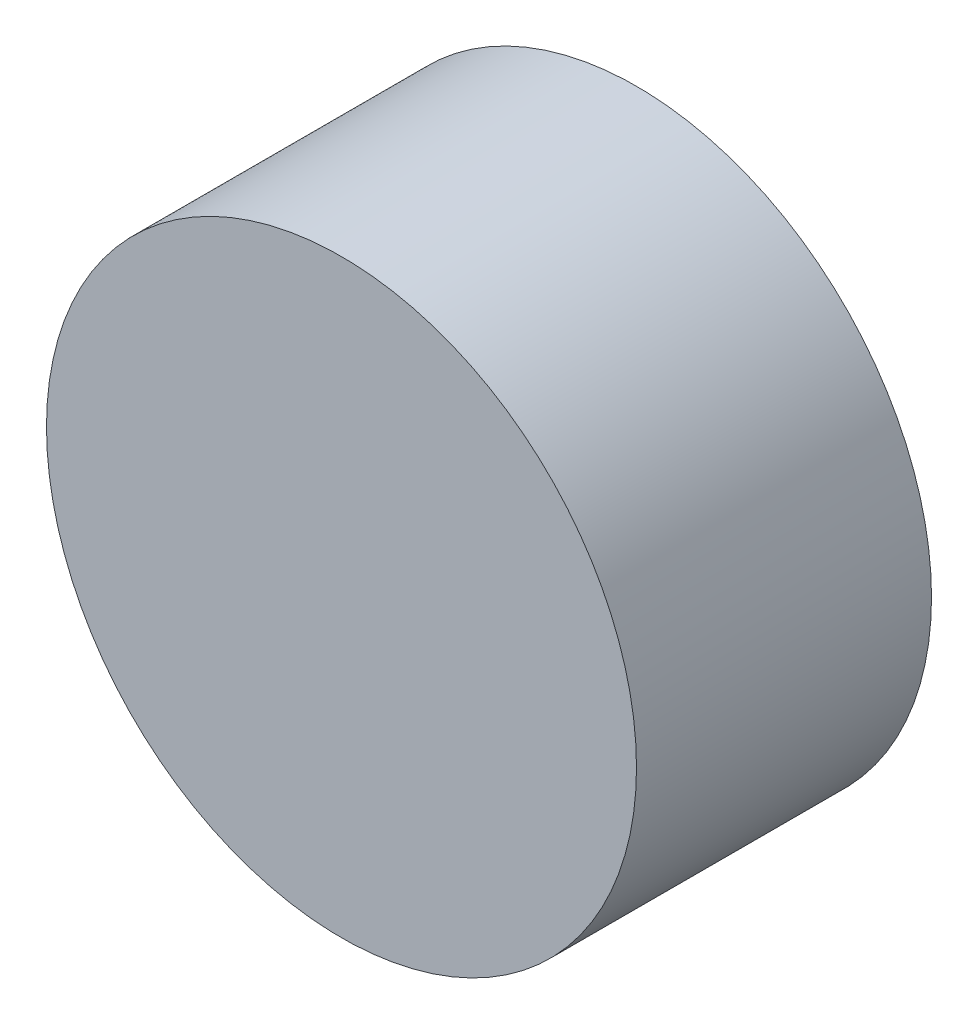
SolidWorks part; units mm, degrees
ref_plane "Front Plane" through (0, 0, 0) normal (0, 0, 1) x (1, 0, 0)
ref_plane "Top Plane" through (0, 0, 0) normal (0, 1, 0) x (1, 0, 0)
ref_plane "Right Plane" through (0, 0, 0) normal (1, 0, 0) x (0, 0, -1)
sketch "Sketch1" plane through (0, 0, 0) normal (0, 0, 1) x (1, 0, 0)
  circle A0 centre (0, 0) radius 100
  dimension "D1" = 200
extrude "Boss-Extrude1" add sketch "Sketch1" along normal blind 100
sketch "Sketch2" plane through (0, 0, 0) normal (0, 0, -1) x (-1, 0, 0)
  line L1 (-12.5, -5) -> (12.5, -5)
  line L2 (-12.5, -5) -> (-12.5, 5)
  line L3 (-12.5, 5) -> (12.5, 5)
  line L4 (12.5, -5) -> (12.5, 5)
  line L5 (-12.5, -5) -> (12.5, 5) construction
  line L6 (-12.5, 5) -> (12.5, -5) construction
  point P0 (0, 0)
  dimension "D1" = 25
  dimension "D2" = 10
extrude "Boss-Extrude2" add sketch "Sketch2" along normal blind 20 and the other way blind 20
sketch "Sketch4" plane through (0, -5, 0) normal (0, -1, 0) x (1, 0, 0)
  circle A0 centre (0, -10) radius 5
  dimension "D1" = 10
extrude "Cut-Extrude1" cut sketch "Sketch4" against normal blind 20
sketch "Sketch6" plane through (0, 0, 0) normal (1, 0, 0) x (0, 0, -1)
  line L0 (0, 0) -> (-100, 0) construction
  point P1 (0, 0)
